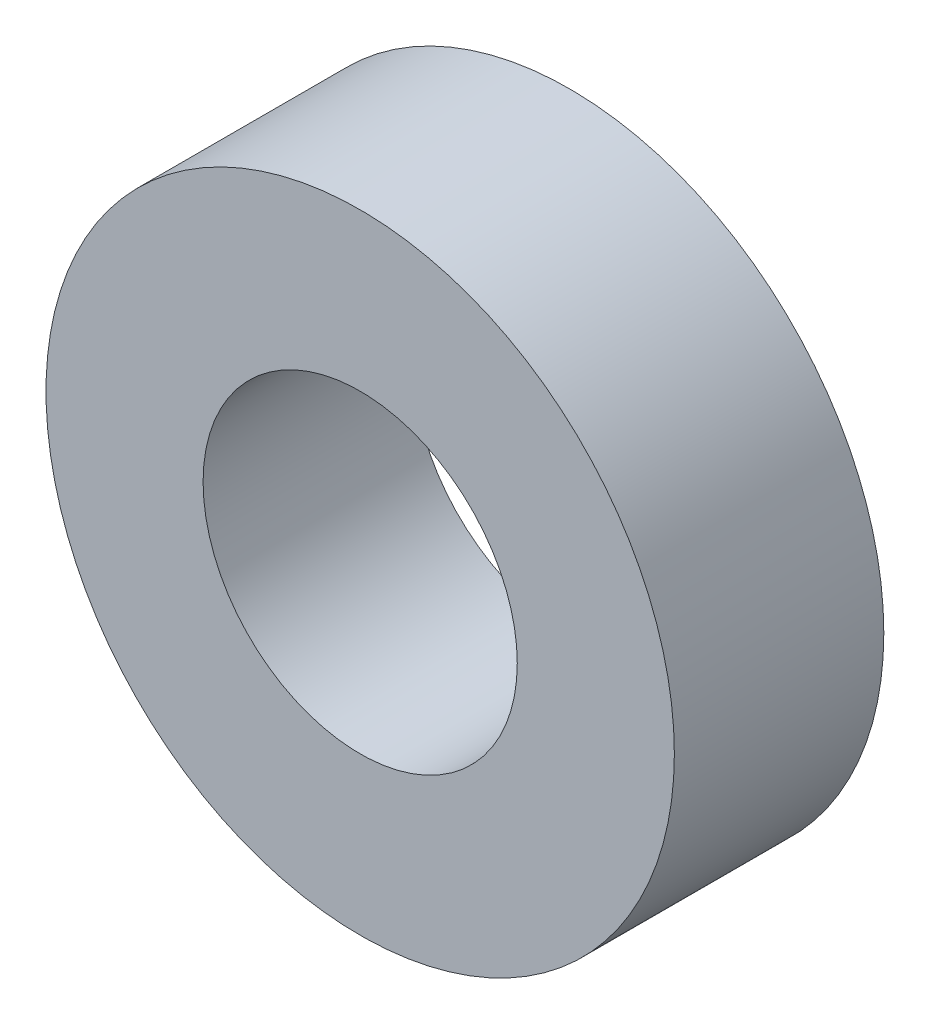
SolidWorks part; units mm, degrees
ref_plane "Спереди" through (0, 0, 0) normal (0, 0, 1) x (1, 0, 0)
ref_plane "Сверху" through (0, 0, 0) normal (0, 1, 0) x (1, 0, 0)
ref_plane "Справа" through (0, 0, 0) normal (1, 0, 0) x (0, 0, -1)
sketch "Эскиз1" plane through (0, 0, 0) normal (0, 1, 0) x (1, 0, 0)
  line L0 (-3, 0) -> (-6, 0)
  line L1 (-6, 0) -> (-6, 4)
  line L2 (-6, 4) -> (-3, 4)
  line L3 (-3, 4) -> (-3, 0)
  line L4 (0, 0) -> (0, 12544.7981) construction
  circle A0 centre (-4.5, 2.5) radius 0.5
  dimension "D4" = 1
  dimension "D1" = 3
  dimension "D2" = 6
  dimension "D3" = 4
  dimension "D5" = 1.5
  dimension "D6" = 1.5
revolve "Повернуть1" add sketch "Эскиз1" angle 360 about L4
